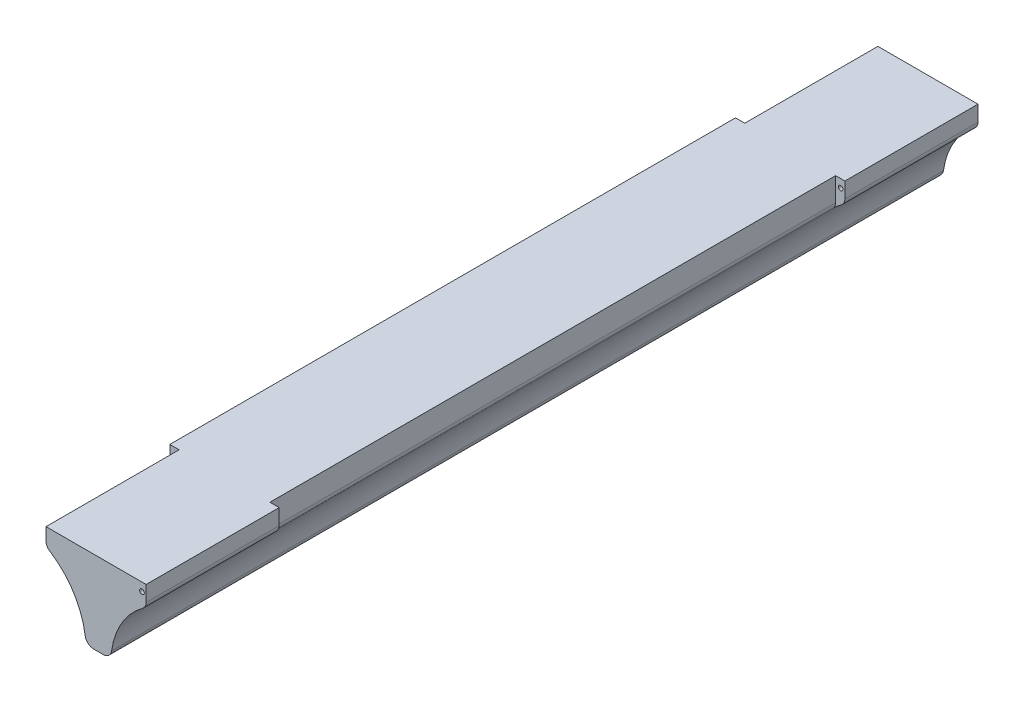
SolidWorks part; units mm, degrees
ref_plane "Front Plane" through (0, 0, 0) normal (0, 0, 1) x (1, 0, 0)
ref_plane "Top Plane" through (0, 0, 0) normal (0, 1, 0) x (1, 0, 0)
ref_plane "Right Plane" through (0, 0, 0) normal (1, 0, 0) x (0, 0, -1)
sketch "Sketch1" plane through (0, 0, 0) normal (0, 0, 1) x (1, 0, 0)
  line L10 (-2.8692, 3.0685) -> (2.8692, 3.0685)
  line L11 (2.8692, 3.0685) -> (2.8692, 1.8721)
  line L12 (-2.8692, 3.0685) -> (-3.7066, 3.0685)
  line L13 (-3.7066, 3.0685) -> (-3.7066, 2.3122)
  arc A0 (2.8692, 1.8721) -> (1.9636, 1.0919) centre (5.4739, -2.0668) ccw
  arc A1 (1.9636, 1.0919) -> (0.796, -1.4211) centre (5.4739, -2.0668) ccw
  arc A2 (-0.796, -1.4211) -> (-1.9636, 1.0919) centre (-5.4739, -2.0668) ccw
  arc A3 (0.2713, -1.872) -> (-0.2713, -1.872) centre (0, -21.4602) ccw
  arc A4 (0.2713, -1.872) -> (0.796, -1.4211) centre (0.2785, -1.3497) ccw
  arc A5 (-0.796, -1.4211) -> (-0.2713, -1.872) centre (-0.2785, -1.3497) ccw
  arc A6 (-1.9636, 1.0919) -> (-3.7066, 2.3122) centre (-5.4739, -2.0668) ccw
  arc A7 (2.8692, 1.8721) -> (1.9636, 1.0919) centre (5.4739, -2.0668) ccw
  arc A8 (1.9636, 1.0919) -> (0.796, -1.4211) centre (5.4739, -2.0668) ccw
  arc A9 (-0.796, -1.4211) -> (-1.9636, 1.0919) centre (-5.4739, -2.0668) ccw
  arc A10 (0.2713, -1.872) -> (-0.2713, -1.872) centre (0, -21.4602) ccw
  arc A11 (0.2713, -1.872) -> (0.796, -1.4211) centre (0.2785, -1.3497) ccw
  arc A12 (-0.796, -1.4211) -> (-0.2713, -1.872) centre (-0.2785, -1.3497) ccw
  arc A13 (-1.9636, 1.0919) -> (-2.8692, 1.8721) centre (-5.4739, -2.0668) ccw
  circle A118 centre (-3.4388, 2.465) radius 0.1258
  circle A119 centre (2.6192, 2.5685) radius 0.1393
  dimension "D3" = 0.5
  dimension "D5" = 0.25
extrude "Boss-Extrude1" add sketch "Sketch1" along normal mid plane 50 contours A6 A2 A5 A3 A4 A1 A0 L11 L10 L12 L13 A119 A118
sketch "Sketch9" plane through (0, 0, 0) normal (0, 0, 1) x (1, 0, 0)
  line L1 (2.8692, 3.0685) -> (2.3111, 3.0685)
  line L2 (2.8692, 3.0685) -> (2.8692, 1.2498)
  line L3 (2.8692, 1.2498) -> (2.3111, 1.2498)
  line L4 (2.3111, 3.0685) -> (2.3111, 1.2498)
  dimension "D1" = 0.5581
extrude "Cut-Extrude6" cut sketch "Sketch9" along normal offset from surface 8 and the other way offset from surface (17 mm away) 8 contours L2 L3 L4 L1 up to face at (-0.191, 0.5191, 25) other way up to face at (-0.191, 0.5191, -25)
sketch "Sketch10" plane through (0, 0, 0) normal (0, 0, 1) x (1, 0, 0)
  line L0 (-3.1484, 3.0685) -> (-3.7066, 3.0685)
  line L1 (-3.1484, 3.0685) -> (-3.1484, 2.0431)
  line L3 (-3.7066, 3.0685) -> (-3.7066, 2.3122)
  circle A0 centre (-3.4388, 2.465) radius 0.1258 construction
  circle A1 centre (-3.4388, 2.465) radius 0.1258
  arc A2 (-1.9636, 1.0919) -> (-3.7066, 2.3122) centre (-5.4739, -2.0668) ccw construction
  arc A3 (-3.1484, 2.0431) -> (-3.7066, 2.3122) centre (-5.4739, -2.0668) ccw
sketch "Sketch11" plane through (0, 0, 17) normal (0, 0, -1) x (-1, 0, 0)
  line L0 (3.7066, 3.0685) -> (3.7066, 2.3122) construction
  line L1 (2.8692, 3.0685) -> (3.7066, 3.0685) construction
  line L2 (3.1484, 3.0685) -> (3.1484, 2.0431) construction
  line L3 (3.7066, 3.0685) -> (3.7066, 2.3122)
  line L4 (3.1484, 3.0685) -> (3.7066, 3.0685)
  line L5 (3.1484, 3.0685) -> (3.1484, 2.0431)
  arc A0 (3.7066, 2.3122) -> (1.9636, 1.0919) centre (5.4739, -2.0668) ccw construction
  circle A1 centre (3.4388, 2.465) radius 0.1258 construction
  arc A2 (3.7066, 2.3122) -> (3.1484, 2.0431) centre (5.4739, -2.0668) ccw
  circle A3 centre (3.4388, 2.465) radius 0.1258
  circle A4 centre (-2.6192, 2.5685) radius 0.1393 construction
  circle A5 centre (-2.6192, 2.5685) radius 0.1393
extrude "Cut-Extrude7" cut sketch "Sketch11" against normal blind 8
sketch "Sketch13" plane through (0, 0, 25) normal (0, 0, 1) x (1, 0, 0)
  circle A1 centre (-3.4388, 2.465) radius 0.1258
  circle A2 centre (-3.4388, 2.465) radius 0.1258
  dimension "D1" = 0
extrude "Cut-Extrude12" cut sketch "Sketch13" against normal blind 1
mirror "Mirror1" about plane through (0, 0, 0) normal (0, 0, 1) of "Cut-Extrude7", "Cut-Extrude12"
fillet "Fillet3" radius 0.5 6 edges at (2.8692, 1.8721, -21) (2.8692, 1.8721, 21) (-3.7066, 2.3122, 0) (2.3111, 1.4398, 0) (-3.1484, 2.0431, -21) (-3.1484, 2.0431, 21)
